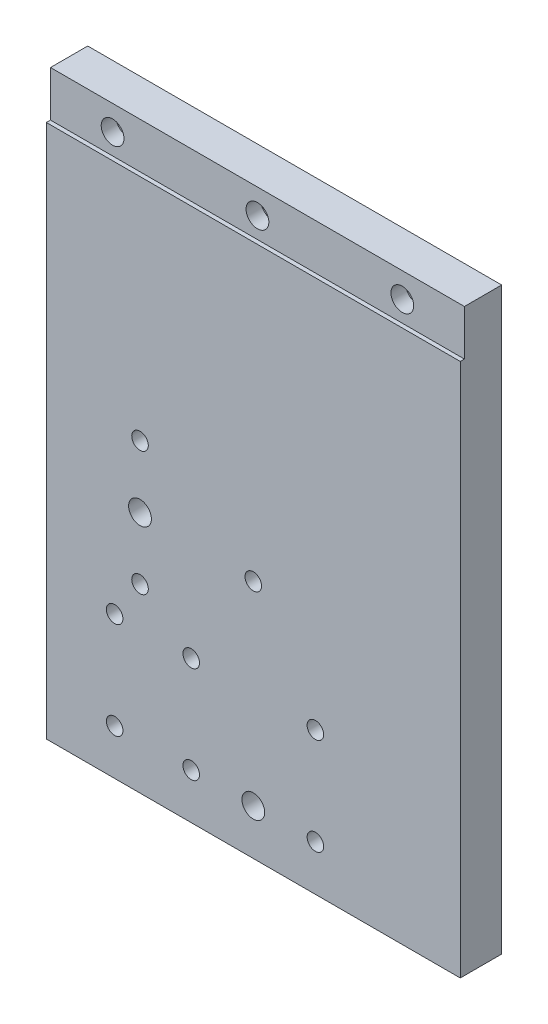
SolidWorks part; units mm, degrees
material "3.3547 (EN-AW 5083)"
ref_plane "Vorne" through (0, 0, 0) normal (0, 0, 1) x (1, 0, 0)
ref_plane "Oben" through (0, 0, 0) normal (0, 1, 0) x (1, 0, 0)
ref_plane "Rechts" through (0, 0, 0) normal (1, 0, 0) x (0, 0, -1)
sketch "Skizze1" plane through (0, 0, 0) normal (0, 0, 1) x (1, 0, 0)
  line L0 (0, -5.5) -> (0, 5.5) construction
  line L1 (-50, 70) -> (50, 70)
  line L2 (-50, 70) -> (-50, -70)
  line L3 (-50, -70) -> (50, -70)
  line L4 (50, 70) -> (50, -70)
  line L5 (-50, 70) -> (50, -70) construction
  line L6 (-50, -70) -> (50, 70) construction
  point P0 (0, 0)
  dimension "D1" = 140
  dimension "D2" = 100
extrude "Aufsatz-Linear austragen1" add sketch "Skizze1" along normal blind 10
hole_wizard "Stirnsenkung für M5 Zylinderschraube mit Innensechskant1" positions "Skizze6" profile "Skizze7" counterbore size "M5" standard "DIN" end condition through all
sketch "Skizze6" plane through (0, 0, 0) normal (0, 0, -1) x (-1, 0, 0)
  line L0 (0, 5.5) -> (0, -5.5) construction
  line L1 (-50, 70) -> (50, 70) construction
  point P0 (0, 64)
  point P4 (35, 64)
  point P6 (-35, 64)
  dimension "D1" = 6
  dimension "D2" = 35
  dimension "D3" = 35
sketch "Skizze7" plane through (0, 64, 0) normal (1, 0, 0) x (0, 1, 0)
  line L0 (0, 0) -> (0, 10)
  line L1 (0, 10) -> (2.75, 10)
  line L3 (2.75, 10) -> (2.75, 5.4)
  line L4 (2.75, 5.4) -> (5, 5.4)
  line L5 (5, 5.4) -> (5, 0)
  line L7 (5, 0) -> (0, 0)
  line L11 (0, -6.35) -> (0, 107.95) construction
  dimension "Bohrerdurchmesser" = 5.5
  dimension "Bohrungstiefe" = 10
  dimension "Senkdurchmesser2" = 10
  dimension "Senktiefe2" = 5.4
sketch "Skizze8" plane through (0, 0, 10) normal (0, 0, 1) x (1, 0, 0)
  line L0 (50, -70) -> (50, 70) construction
  line L1 (-50, 70) -> (50, 70)
  line L2 (-50, 70) -> (-50, 59)
  line L3 (-50, 59) -> (50, 59)
  line L4 (50, 70) -> (50, 59)
  dimension "D1" = 11
extrude "Schnitt-Linear austragen1" cut sketch "Skizze8" against normal blind 1
hole_wizard "Stirnsenkung für M5 Zylinderschraube mit Innensechskant2" positions "Skizze9" profile "Skizze10" counterbore size "M5" standard "DIN" end condition through all
sketch "Skizze9" plane through (0, 0, 0) normal (0, 0, -1) x (-1, 0, 0)
  line L0 (0, 5.5) -> (0, -5.5) construction
  line L1 (5.5, 0) -> (-5.5, 0) construction
  point P0 (0, -59)
  point P4 (27.37, -11.28)
  dimension "D1" = 59
  dimension "D2" = 27.37
  dimension "D3" = 11.28
sketch "Skizze10" plane through (0, -59, 0) normal (1, 0, 0) x (0, 1, 0)
  line L0 (0, 0) -> (0, 10)
  line L1 (0, 10) -> (2.75, 10)
  line L3 (2.75, 10) -> (2.75, 5.4)
  line L4 (2.75, 5.4) -> (5, 5.4)
  line L5 (5, 5.4) -> (5, 0)
  line L7 (5, 0) -> (0, 0)
  line L11 (0, -6.35) -> (0, 107.95) construction
  dimension "Bohrerdurchmesser" = 5.5
  dimension "Bohrungstiefe" = 10
  dimension "Senkdurchmesser2" = 10
  dimension "Senktiefe2" = 5.4
hole_wizard "Ø4.0 (4) Durchmesser Bohrung1" positions "Skizze11" profile "Skizze12" hole size "Ø4.0" standard "DIN" end condition through all
sketch "Skizze11" plane through (0, 0, 0) normal (0, 0, -1) x (-1, 0, 0)
  line L0 (0, -59) -> (-15, -59) construction
  line L2 (27.37, -11.28) -> (27.37, -26.28) construction
  circle A0 centre (0, -59) radius 2.75 construction
  circle A1 centre (27.37, -11.28) radius 2.75 construction
  point P0 (15, -59)
  point P2 (-15, -59)
  point P4 (27.37, -26.28)
  point P6 (27.37, 3.72)
  dimension "D1" = 15
  dimension "D3" = 15
  dimension "D2" = 30
  dimension "D4" = 30
sketch "Skizze12" plane through (-15, -59, 0) normal (1, 0, 0) x (0, 1, 0)
  line L0 (0, 0) -> (0, 10)
  line L1 (0, 10) -> (2, 10)
  line L2 (2, 10) -> (2, 0)
  line L5 (2, 0) -> (0, 0)
  line L11 (0, -6.35) -> (0, 107.95) construction
  dimension "Bohrerdurchmesser" = 4
  dimension "Bohrungstiefe" = 10
hole_wizard "Ø4.0 (4) Durchmesser Bohrung2" positions "Skizze13" profile "Skizze14" hole size "Ø4.0" standard "DIN" end condition through all
sketch "Skizze13" plane through (0, 0, 0) normal (0, 0, -1) x (-1, 0, 0)
  line L0 (0, 5.5) -> (0, -5.5) construction
  line L1 (50, -70) -> (-50, -70) construction
  point P0 (15, -35.6)
  point P2 (-15, -35.6)
  dimension "D1" = 15
  dimension "D2" = 30
  dimension "D3" = 34.4
sketch "Skizze14" plane through (-15, -35.6, 0) normal (1, 0, 0) x (0, 1, 0)
  line L0 (0, 0) -> (0, 10)
  line L1 (0, 10) -> (2, 10)
  line L2 (2, 10) -> (2, 0)
  line L5 (2, 0) -> (0, 0)
  line L11 (0, -6.35) -> (0, 107.95) construction
  dimension "Bohrerdurchmesser" = 4
  dimension "Bohrungstiefe" = 10
hole_wizard "Ø4.0 (4) Durchmesser Bohrung3" positions "Skizze15" profile "Skizze16" hole size "Ø4.0" standard "DIN" end condition through all
sketch "Skizze15" plane through (0, 0, 10) normal (0, 0, 1) x (1, 0, 0)
  line L0 (-50, 59) -> (-50, -70) construction
  line L1 (-50, -70) -> (50, -70) construction
  point P0 (-33.5, -35.6)
  point P2 (-33.5, -59)
  dimension "D1" = 16.5
  dimension "D2" = 11
  dimension "D3" = 23.4
sketch "Skizze16" plane through (-33.5, -35.6, 10) normal (1, 0, 0) x (0, -1, 0)
  line L0 (0, 0) -> (0, 10)
  line L1 (0, 10) -> (2, 10)
  line L2 (2, 10) -> (2, 0)
  line L5 (2, 0) -> (0, 0)
  line L11 (0, -6.35) -> (0, 107.95) construction
  dimension "Bohrerdurchmesser" = 4
  dimension "Bohrungstiefe" = 10
hole_wizard "Ø4.0 (4) Durchmesser Bohrung4" positions "Skizze17" profile "Skizze18" hole size "Ø4.0" standard "DIN" end condition through all
sketch "Skizze17" plane through (0, 0, 10) normal (0, 0, 1) x (1, 0, 0)
  line L1 (0, -5.5) -> (0, 5.5) construction
  line L2 (-50, -70) -> (50, -70) construction
  point P0 (0, -12)
  dimension "D1" = 58
sketch "Skizze18" plane through (0, -12, 10) normal (1, 0, 0) x (0, -1, 0)
  line L0 (0, 0) -> (0, 10)
  line L1 (0, 10) -> (2, 10)
  line L2 (2, 10) -> (2, 0)
  line L5 (2, 0) -> (0, 0)
  line L11 (0, -6.35) -> (0, 107.95) construction
  dimension "Bohrerdurchmesser" = 4
  dimension "Bohrungstiefe" = 10
